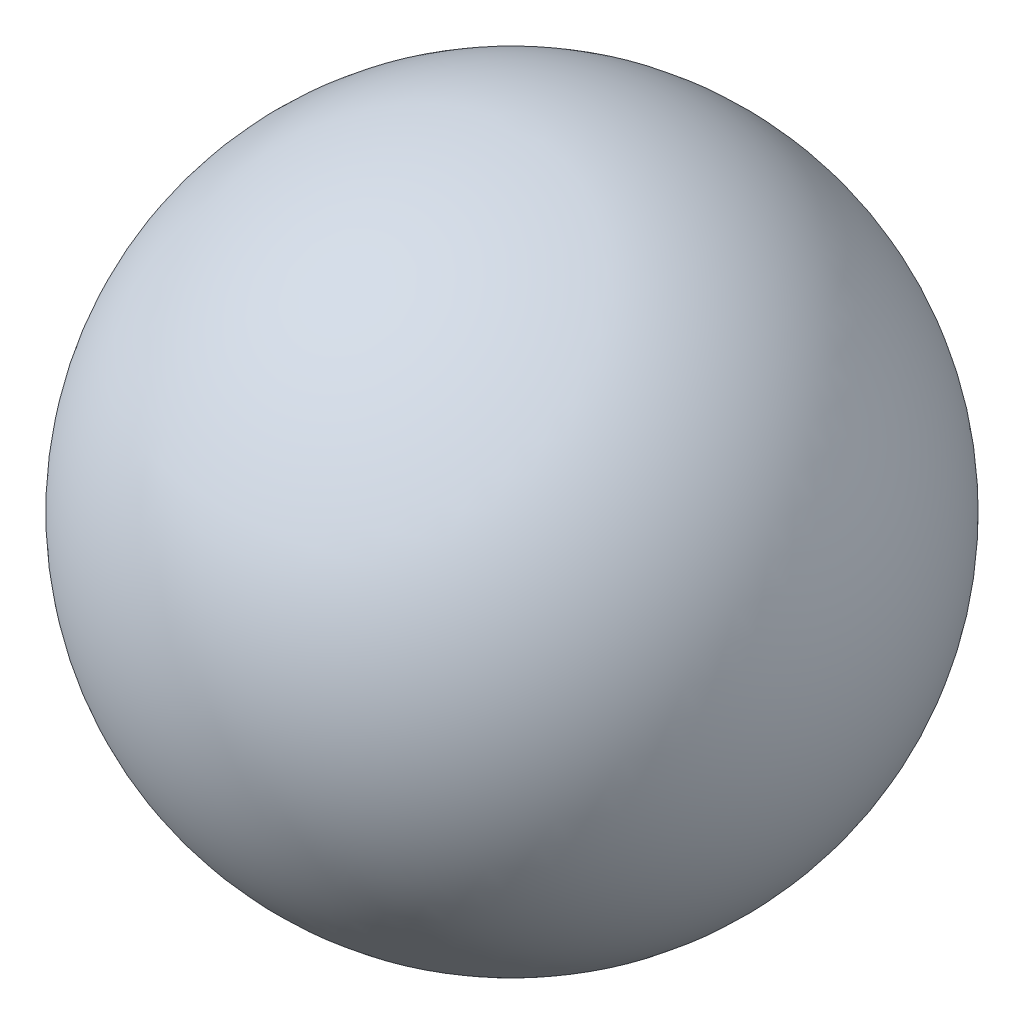
SolidWorks part; units mm, degrees
ref_plane "Piano frontale" through (0, 0, 0) normal (0, 0, 1) x (1, 0, 0)
ref_plane "Piano superiore" through (0, 0, 0) normal (0, 1, 0) x (1, 0, 0)
ref_plane "Piano destro" through (0, 0, 0) normal (1, 0, 0) x (0, 0, -1)
sketch "Schizzo1" plane through (0, 0, 0) normal (0, 0, 1) x (1, 0, 0)
  line L0 (0, 0) -> (0, 120)
  arc A0 (0, 120) -> (0, 0) centre (0, 60) ccw
  dimension "D1" = 60
revolve "Rivoluzione1" add sketch "Schizzo1" angle 360 about L0
sketch "Schizzo2" plane through (0, 0, 0) normal (1, 0, 0) x (0, 0, -1)
  point P0 (0, 60)
  dimension "D1" = 60
